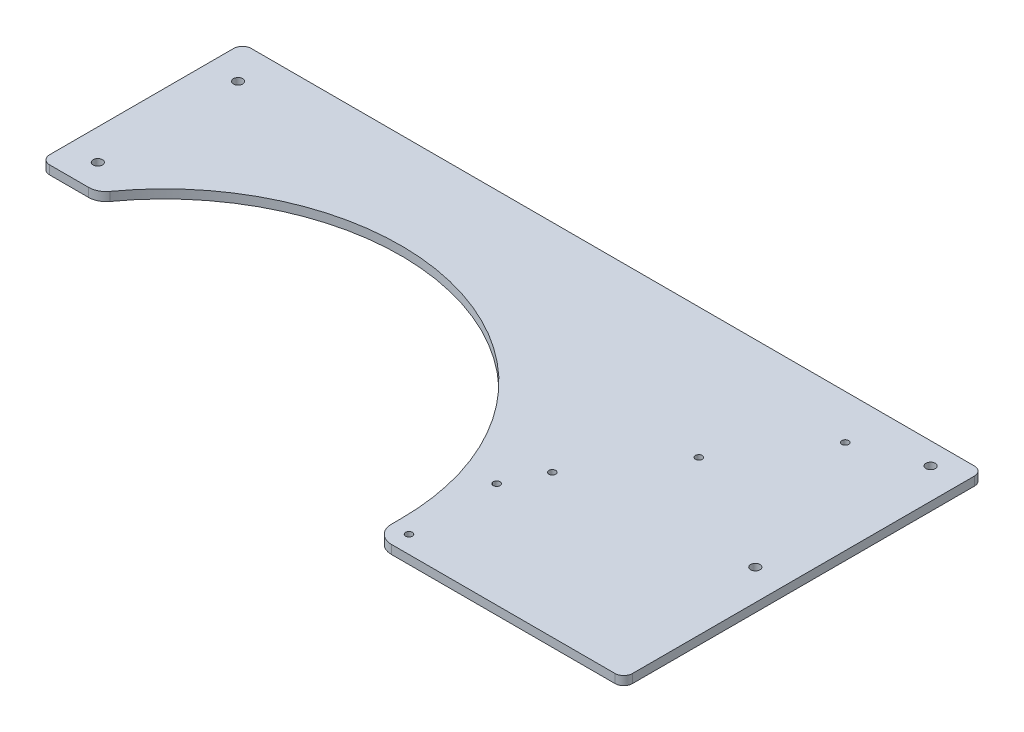
SolidWorks part; units mm, degrees
material "PE High Density"
ref_plane "Front Plane" through (0, 0, 0) normal (0, 0, 1) x (1, 0, 0)
ref_plane "Top Plane" through (0, 0, 0) normal (0, 1, 0) x (1, 0, 0)
ref_plane "Right Plane" through (0, 0, 0) normal (1, 0, 0) x (0, 0, -1)
sketch "Sketch1" plane through (0, 0, 0) normal (0, 1, 0) x (1, 0, 0)
  line L0 (-268.2875, -15.875) -> (-233.3625, -15.875)
  line L1 (-227.0125, -130.175) -> (268.2875, -130.175)
  line L2 (-268.2875, -15.875) -> (-268.2875, 130.175)
  line L3 (-268.2875, 130.175) -> (268.2875, 130.175)
  line L4 (268.2875, -130.175) -> (268.2875, 130.175)
  line L5 (-268.2875, -130.175) -> (268.2875, 130.175) construction
  line L6 (-268.2875, 130.175) -> (268.2875, -130.175) construction
  line L7 (-227.0125, -22.225) -> (-227.0125, -130.175)
  arc A0 (-233.3625, -15.875) -> (-227.0125, -22.225) centre (-233.3625, -22.225) cw
  point P0 (0, 0)
  point P14 (-227.0125, -15.875)
  dimension "D5" = 6.35
  dimension "D1" = 536.575
  dimension "D2" = 260.35
  dimension "D3" = 41.275
  dimension "D4" = 114.3
extrude "Boss-Extrude1" add sketch "Sketch1" along normal blind 6.35
sketch "Sketch2" plane through (0, 6.35, 0) normal (0, 1, 0) x (1, 0, 0)
  line L0 (-227.0125, -130.175) -> (268.2875, -130.175) construction
  line L1 (-227.0125, -22.225) -> (-227.0125, -130.175) construction
  line L2 (268.2875, -130.175) -> (268.2875, 130.175) construction
  line L3 (-268.2875, 130.175) -> (-268.2875, -15.875) construction
  line L4 (268.2875, 130.175) -> (-268.2875, 130.175) construction
  line L5 (200.4456, 98.1535) -> (113.0325, -26.6852) construction
  line L6 (100.0125, -53.975) -> (100.0125, -117.475) construction
  point P0 (-220.6625, -117.475)
  point P1 (-220.6625, -53.975)
  point P2 (-246.0625, 3.175)
  point P3 (-246.0625, 104.775)
  point P12 (246.0625, 114.3381)
  point P13 (246.0625, -12.6619)
  point P16 (100.0125, -53.975)
  point P17 (100.0125, -117.475)
  point P18 (113.0325, -26.6852)
  point P19 (156.7391, 35.7341)
  point P20 (200.4456, 98.1535)
  dimension "D1" = 63.5
  dimension "D2" = 12.7
  dimension "D3" = 6.35
  dimension "D4" = 101.6
  dimension "D5" = 25.4
  dimension "D6" = 22.225
  dimension "D7" = 127
  dimension "D8" = 22.225
  dimension "D9" = 15.8369
  dimension "D10" = 152.4
  dimension "D11" = 63.5
  dimension "D12" = 12.7
  dimension "D13" = 145
  dimension "D14" = 168.275
  dimension "D15" = 13.02
  dimension "D16" = 103.4898
hole_wizard "17/64 (0.26563) Diameter Hole1" positions "Sketch3" profile "Sketch4" hole size "17/64" standard "ANSI Inch" end condition through all
sketch "Sketch3" plane through (0, 6.35, 0) normal (0, 1, 0) x (1, 0, 0)
  point P0 (-246.0625, 104.775)
  point P3 (-246.0625, 3.175)
  point P6 (-220.6625, -53.975)
  point P9 (-220.6625, -117.475)
  point P14 (246.0625, 114.3381)
  point P17 (246.0625, -12.6619)
sketch "Sketch4" plane through (-246.0625, 6.35, -104.775) normal (1, 0, 0) x (0, 0, 1)
  line L0 (0, 0) -> (0, 6.35)
  line L1 (0, 6.35) -> (3.3735, 6.35)
  line L2 (3.3735, 6.35) -> (3.3735, 0)
  line L5 (3.3735, 0) -> (0, 0)
  line L11 (0, -6.35) -> (0, 107.95) construction
  dimension "Thru Hole Dia." = 6.747
  dimension "Thru Hole Depth" = 6.35
fillet "Fillet1" radius 6.35 5 edges at (268.2875, 3.175, -130.175) (268.2875, 3.175, 130.175) (-227.0125, 3.175, 130.175) (-268.2875, 3.175, 15.875) (-268.2875, 3.175, -130.175)
hole_wizard "#10 (0.1935) Diameter Hole1" positions "Sketch6" profile "Sketch7" hole size "#10" standard "ANSI Inch" end condition through all
sketch "Sketch6" plane through (0, 6.35, 0) normal (0, 1, 0) x (1, 0, 0)
  point P0 (200.4456, 98.1535)
  point P3 (156.7391, 35.7341)
  point P6 (113.0325, -26.6852)
  point P9 (100.0125, -53.975)
  point P12 (100.0125, -117.475)
sketch "Sketch7" plane through (200.4456, 6.35, -98.1535) normal (1, 0, 0) x (0, 0, 1)
  line L0 (0, 0) -> (0, 6.35)
  line L1 (0, 6.35) -> (2.4574, 6.35)
  line L2 (2.4574, 6.35) -> (2.4574, 0)
  line L5 (2.4574, 0) -> (0, 0)
  line L11 (0, -6.35) -> (0, 107.95) construction
  dimension "Thru Hole Dia." = 4.9149
  dimension "Thru Hole Depth" = 6.35
sketch "Sketch8" plane through (0, 6.35, 0) normal (0, 1, 0) x (1, 0, 0)
  line L0 (87.3125, -130.175) -> (87.3125, -110.6476)
  line L1 (-220.6625, -130.175) -> (261.9375, -130.175) construction
  line L2 (-233.3625, -15.875) -> (-227.0125, -15.875)
  line L3 (-227.0125, -22.225) -> (-227.0125, -123.825) construction
  line L4 (-220.6625, -130.175) -> (261.9375, -130.175)
  line L5 (-227.0125, -22.225) -> (-227.0125, -123.825)
  arc A0 (-227.0125, -15.875) -> (87.3125, -110.6476) centre (-84.1375, -110.6476) cw
  circle A1 centre (100.0125, -117.475) radius 2.4574 construction
  arc A2 (-227.0125, -123.825) -> (-220.6625, -130.175) centre (-220.6625, -123.825) ccw construction
  arc A3 (-227.0125, -22.225) -> (-233.3625, -15.875) centre (-233.3625, -22.225) ccw construction
  arc A4 (-227.0125, -123.825) -> (-220.6625, -130.175) centre (-220.6625, -123.825) ccw
  arc A5 (-227.0125, -22.225) -> (-233.3625, -15.875) centre (-233.3625, -22.225) ccw
  circle M9 centre (-220.6625, -53.975) radius 3.3735
  circle M10 centre (-220.6625, -117.475) radius 3.3735
  arc M20 (-233.3625, -15.875) -> (-227.0125, -22.225) centre (-233.3625, -22.225) cw
  line M21 (-227.0125, -22.225) -> (-227.0125, -123.825)
  arc M22 (-227.0125, -123.825) -> (-220.6625, -130.175) centre (-220.6625, -123.825) ccw
  line M23 (-220.6625, -130.175) -> (261.9375, -130.175)
  dimension "D1" = 171.45
  dimension "D2" = 12.7
  dimension "D3" = 0
extrude "Cut-Extrude1" cut sketch "Sketch8" against normal through all contours A0 L2 L0 M20 M21 M22 M23 M9 M10
fillet "Fillet2" radius 12.7 2 edges at (87.3125, 3.175, 130.175) (-227.0125, 3.175, 15.875)
